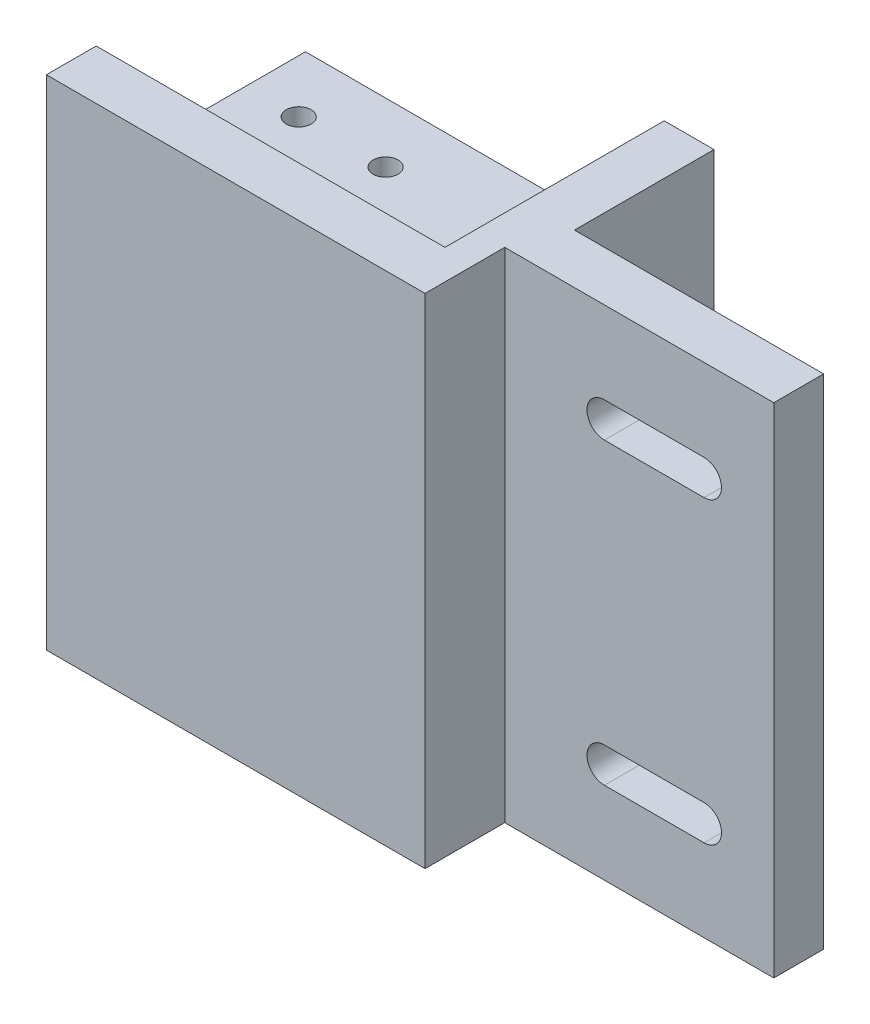
SolidWorks part; units mm, degrees
ref_plane "Front Plane" through (0, 0, 0) normal (0, 0, 1) x (1, 0, 0)
ref_plane "Top Plane" through (0, 0, 0) normal (0, 1, 0) x (1, 0, 0)
ref_plane "Right Plane" through (0, 0, 0) normal (1, 0, 0) x (0, 0, -1)
sketch "Sketch1" plane through (0, 0, 0) normal (0, 0, 1) x (1, 0, 0)
  line L1 (-50, -25) -> (50, -25)
  line L2 (-50, -25) -> (-50, 25)
  line L3 (-50, 25) -> (50, 25)
  line L4 (50, -25) -> (50, 25)
  line L5 (-50, -25) -> (50, 25) construction
  line L6 (-50, 25) -> (50, -25) construction
  point P0 (0, 0)
  dimension "D1" = 100
  dimension "D2" = 50
extrude "Boss-Extrude1" add sketch "Sketch1" along normal blind 5
sketch "Sketch2" plane through (0, 0, 0) normal (0, 0, 1) x (1, 0, 0)
  line L1 (25, -25) -> (20, -25)
  line L2 (25, -25) -> (25, 25)
  line L3 (25, 25) -> (20, 25)
  line L4 (20, -25) -> (20, 25)
  line L5 (25, -25) -> (20, 25) construction
  line L6 (25, 25) -> (20, -25) construction
  point P0 (22.5, 0)
  point P1 (22.5, 0)
  dimension "D1" = 5
  dimension "D2" = 50
  dimension "D3" = 20
extrude "Boss-Extrude2" add sketch "Sketch2" against normal blind 22
sketch "Sketch5" plane through (0, 0, 0) normal (0, 0, 1) x (1, 0, 0)
  line L0 (20, 25) -> (20, -25) construction
  line L1 (-10, 19) -> (15, 19)
  line L2 (-10, 19) -> (-10, 15)
  line L3 (-10, 15) -> (15, 15)
  line L4 (15, 19) -> (15, 15)
  line L5 (-10, 19) -> (15, 15) construction
  line L6 (-10, 15) -> (15, 19) construction
  line L7 (-50, -25) -> (20, -25) construction
  dimension "D1" = 5
  dimension "D2" = 25
  dimension "D3" = 4
  dimension "D4" = 40
extrude "Boss-Extrude3" add sketch "Sketch5" against normal blind 16
sketch "Sketch6" plane through (0, 19, 0) normal (0, 1, 0) x (1, 0, 0)
  line L0 (15, 16) -> (-10, 16) construction
  line L1 (-10, 16) -> (-10, 0) construction
  circle A0 centre (-4.68, 10) radius 1.25
  circle A1 centre (4.04, 10) radius 1.25
  dimension "D1" = 2.5
  dimension "D2" = 6
  dimension "D3" = 5.32
  dimension "D4" = 8.72
extrude "Holes-to-fix-level-switch" cut sketch "Sketch6" against normal blind 40
sketch "Sketch10" plane through (0, 0, 0) normal (0, 0, -1) x (-1, 0, 0)
  line L1 (-25, 25) -> (-50, 25)
  line L2 (-25, 25) -> (-25, -25)
  line L3 (-25, -25) -> (-50, -25)
  line L4 (-50, 25) -> (-50, -25)
  line L5 (-25, 25) -> (-50, -25) construction
  line L6 (-25, -25) -> (-50, 25) construction
  point P4 (-37.5, 0)
extrude "Boss-Extrude4" add sketch "Sketch10" along normal blind 8
sketch "Sketch8" plane through (0, 0, 0) normal (0, 0, 1) x (1, 0, 0)
  line L0 (33, 15) -> (43, 15) construction
  line L1 (33, 16.75) -> (43, 16.75)
  line L2 (33, 13.25) -> (43, 13.25)
  line L3 (33, -15) -> (43, -15) construction
  line L4 (33, -13.25) -> (43, -13.25)
  line L5 (33, -16.75) -> (43, -16.75)
  line L6 (25, -25) -> (25, 25) construction
  line L7 (-50, -25) -> (20, -25) construction
  arc A0 (33, 16.75) -> (33, 13.25) centre (33, 15) ccw
  arc A1 (43, 13.25) -> (43, 16.75) centre (43, 15) ccw
  arc A2 (33, -13.25) -> (33, -16.75) centre (33, -15) ccw
  arc A3 (43, -16.75) -> (43, -13.25) centre (43, -15) ccw
  point P2 (38, 15)
  point P9 (38, -15)
  dimension "D3" = 8
  dimension "D4" = 1.75
  dimension "D8" = 1.75
  dimension "D9" = 8
  dimension "D1" = 10
  dimension "D2" = 3.5
  dimension "D5" = 30
  dimension "D6" = 10
  dimension "D7" = 10
extrude "Cut-Extrude2" cut sketch "Sketch8" along normal through all both and the other way through all
sketch "Sketch9" plane through (0, 0, 0) normal (0, 0, -1) x (-1, 0, 0)
  line L0 (50, 25) -> (50, -25) construction
  line L1 (15, -25) -> (50, -25)
  line L2 (15, -25) -> (15, 25)
  line L3 (15, 25) -> (50, 25)
  line L4 (50, -25) -> (50, 25)
  line L5 (15, -25) -> (50, 25) construction
  line L6 (15, 25) -> (50, -25) construction
  line L7 (-20, 25) -> (50, 25) construction
  line L8 (50, -25) -> (-20, -25) construction
  line L9 (10, 19) -> (10, 15) construction
  point P0 (32.5, 0)
  dimension "D1" = 0
  dimension "D2" = 0
  dimension "D3" = 0
  dimension "D4" = 5
extrude "Cut-Extrude3" cut sketch "Sketch9" against normal blind 10
sketch "Sketch11" plane through (0, 0, 5) normal (0, 0, 1) x (1, 0, 0)
  line L0 (50, 25) -> (-15, 25) construction
  line L1 (50, -25) -> (23, -25)
  line L2 (50, -25) -> (50, 25)
  line L3 (50, 25) -> (23, 25)
  line L4 (23, -25) -> (23, 25)
  line L5 (50, -25) -> (23, 25) construction
  line L6 (50, 25) -> (23, -25) construction
  point P4 (36.5, 0)
  point P6 (23.4965, 25)
  dimension "D1" = 50
  dimension "D2" = 27
extrude "Cut-Extrude4" cut sketch "Sketch11" against normal blind 8
